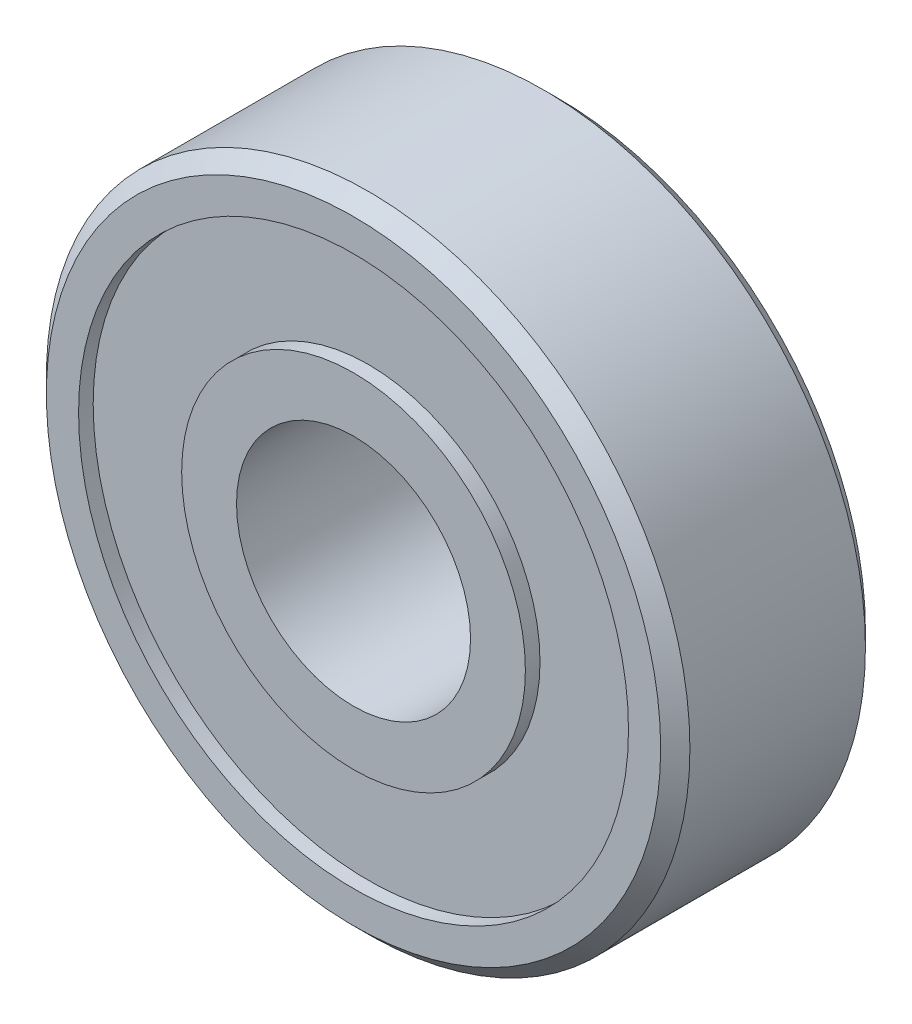
SolidWorks part; units mm, degrees
material "Plain Carbon Steel"
ref_plane "Front Plane" through (0, 0, 0) normal (0, 0, 1) x (1, 0, 0)
ref_plane "Top Plane" through (0, 0, 0) normal (0, 1, 0) x (1, 0, 0)
ref_plane "Right Plane" through (0, 0, 0) normal (1, 0, 0) x (0, 0, -1)
sketch "Sketch1" plane through (0, 0, 0) normal (0, 0, 1) x (1, 0, 0)
  circle A0 centre (0, 0) radius 11
  circle A1 centre (0, 0) radius 4
  dimension "D1" = 22
  dimension "D2" = 8
extrude "Boss-Extrude1" add sketch "Sketch1" along normal mid plane 7
sketch "Sketch2" plane through (0, 0, 3.5) normal (0, 0, 1) x (1, 0, 0)
  circle A0 centre (0, 0) radius 5.875
  circle A1 centre (0, 0) radius 9.4
  dimension "D1" = 18.8
  dimension "D2" = 11.75
extrude "Cut-Extrude1" cut sketch "Sketch2" against normal blind 0.5
sketch "Sketch3" plane through (0, 0, -3.5) normal (0, 0, -1) x (-1, 0, 0)
  circle A0 centre (0, 0) radius 5.875
  circle A1 centre (0, 0) radius 9.4
  dimension "D1" = 18.8
  dimension "D2" = 11.75
extrude "Cut-Extrude2" cut sketch "Sketch3" against normal blind 1
chamfer "Chamfer1" distance 0.5 angle 45 2 edges at (11, 0, -3.5) (11, 0, 3.5)
